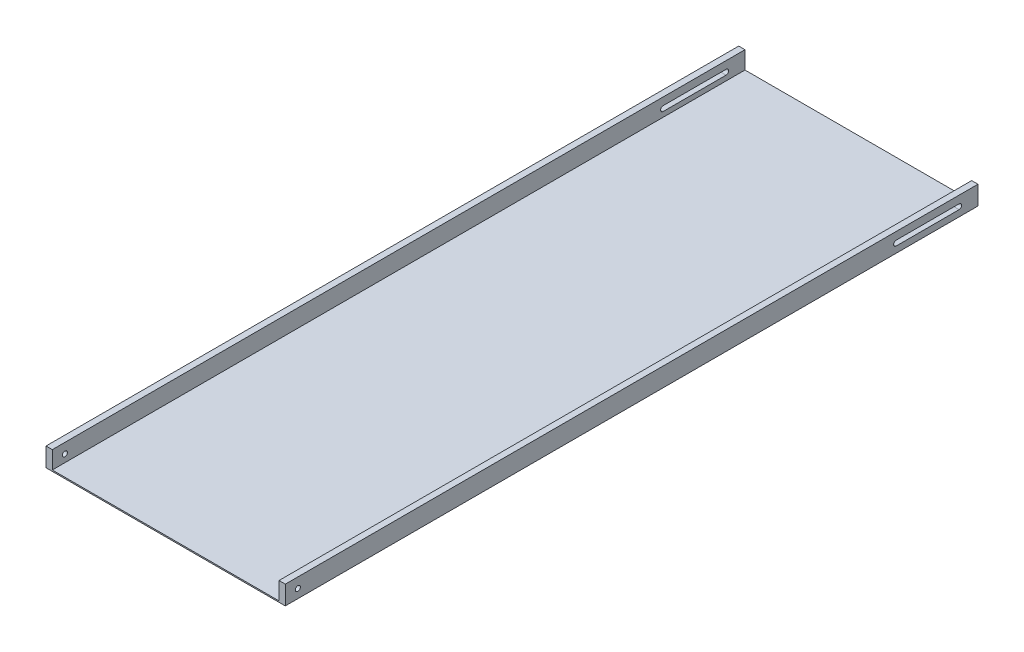
SolidWorks part; units mm, degrees
ref_plane "Front Plane" through (0, 0, 0) normal (0, 0, 1) x (1, 0, 0)
ref_plane "Top Plane" through (0, 0, 0) normal (0, 1, 0) x (1, 0, 0)
ref_plane "Right Plane" through (0, 0, 0) normal (1, 0, 0) x (0, 0, -1)
sketch "Sketch1" plane through (0, 0, 0) normal (0, 0, 1) x (1, 0, 0)
  line L0 (-175.6471, 7.8529) -> (-175.6471, -7.1471)
  line L1 (-175.6471, -7.1471) -> (14.3529, -7.1471)
  line L2 (14.3529, -7.1471) -> (14.3529, 7.8529)
  line L3 (14.3529, 7.8529) -> (9.3529, 7.8529)
  line L4 (9.3529, 7.8529) -> (9.3529, -6.1471)
  line L5 (9.3529, -6.1471) -> (-170.6471, -6.1471)
  line L6 (-170.6471, -6.1471) -> (-170.6471, 7.8529)
  line L7 (-170.6471, 7.8529) -> (-175.6471, 7.8529)
  dimension "D1" = 14
  dimension "D2" = 14
  dimension "D3" = 15
  dimension "D4" = 5
  dimension "D5" = 5
  dimension "D6" = 190
extrude "Boss-Extrude1" add sketch "Sketch1" along normal blind 550
sketch "Sketch2" plane through (14.3529, 0, 0) normal (1, 0, 0) x (0, 0, -1)
  line L0 (-550, -7.1471) -> (0, -7.1471) construction
  line L1 (-550, -7.1471) -> (-550, 7.8529) construction
  point P0 (-540, -0.1471)
  dimension "D1" = 7
  dimension "D2" = 10
hole_wizard "Ø4.0mm Dowel Hole1" positions "Sketch3" profile "Sketch4" hole size "Ø4.0" standard "ANSI Metric" end condition through all
sketch "Sketch3" plane through (14.3529, 0, 0) normal (1, 0, 0) x (0, 0, -1)
  point P0 (-540, -0.1471)
sketch "Sketch4" plane through (14.3529, -0.1471, 540) normal (0, 1, 0) x (0, 0, -1)
  line L0 (0, 0) -> (0, 190)
  line L1 (0, 190) -> (2, 190)
  line L2 (2, 190) -> (2, 0)
  line L5 (2, 0) -> (0, 0)
  line L11 (0, -6.35) -> (0, 107.95) construction
  dimension "Thru Hole Dia." = 4
  dimension "Thru Hole Depth" = 190
sketch "Sketch5" plane through (14.3529, 0, 0) normal (1, 0, 0) x (0, 0, -1)
  line L0 (0, -7.1471) -> (0, 7.8529) construction
  line L1 (-65, 1.8529) -> (-15, 1.8529)
  line L2 (-15, -2.1471) -> (-65, -2.1471)
  line L3 (-550, -7.1471) -> (0, -7.1471) construction
  arc A0 (-15, -2.1471) -> (-15, 1.8529) centre (-15, -0.1471) ccw
  arc A1 (-65, 1.8529) -> (-65, -2.1471) centre (-65, -0.1471) ccw
  point P4 (0, 0.3529)
  dimension "D2" = 4
  dimension "D3" = 4
  dimension "D1" = 15
  dimension "D4" = 50
  dimension "D5" = 5
extrude "Cut-Extrude1" cut sketch "Sketch5" against normal through all
sketch "Sketch6" plane through (0, -6.1471, 0) normal (0, 1, 0) x (1, 0, 0)
  line L0 (9.3529, -550) -> (-170.6471, -550)
  line L1 (9.3529, -550) -> (9.3529, -0.1769)
  line L2 (-170.6471, -550) -> (-170.6471, -0.1769)
  line L3 (9.3529, -0.1769) -> (-170.6471, -0.1769)
